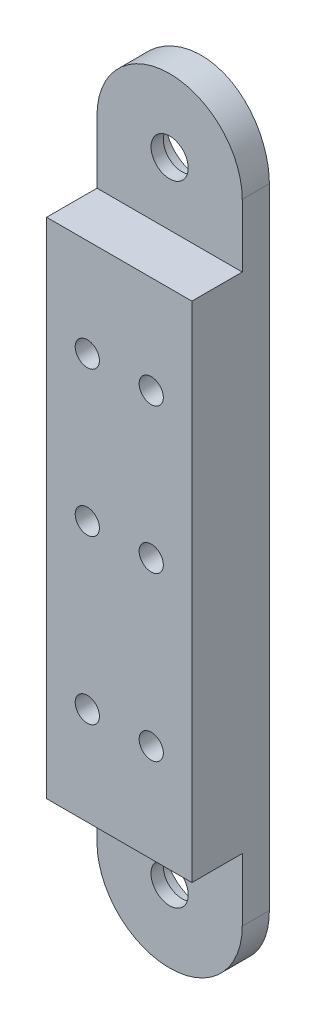
SolidWorks part; units mm, degrees
material "Nylon 101"
ref_plane "Front Plane" through (0, 0, 0) normal (0, 0, 1) x (1, 0, 0)
ref_plane "Top Plane" through (0, 0, 0) normal (0, 1, 0) x (1, 0, 0)
ref_plane "Right Plane" through (0, 0, 0) normal (1, 0, 0) x (0, 0, -1)
other "Stock"
other "Bounding Box"
ref_plane "Default Plane" through (5.3337, 0, -6.6488) normal (-1, 0, 0) x (0, 0, 1)
sketch "Sketch1" plane through (0, 0, 0) normal (0, 1, 0) x (1, 0, 0)
  line L1 (-4.1913, 1.27) -> (5.3337, 1.27)
  line L2 (-4.1913, 1.27) -> (-4.1913, 6.35)
  line L4 (5.3337, 1.27) -> (5.3337, 6.35)
  arc A0 (-4.1913, 6.35) -> (5.3337, 6.35) centre (0.5712, -31.4512) cw
  dimension "D3" = 38.1
  dimension "D1" = 9.525
  dimension "D2" = 5.08
extrude "Main profile" add sketch "Sketch1" along normal blind 50.8
sketch "Sketch2" plane through (0, 0, -1.27) normal (0, 0, 1) x (1, 0, 0)
  line L0 (-4.1913, 50.8) -> (-4.1913, 0) construction
  line L1 (5.3337, 50.8) -> (5.3337, 0) construction
  line L2 (-4.1913, 50.8) -> (5.3337, 50.8) construction
  line L3 (-4.1913, 0) -> (5.3337, 0) construction
  line L4 (-4.1913, 46.0375) -> (-4.1913, 4.7625)
  line L5 (5.3337, 46.0375) -> (5.3337, 4.7625)
  line L10 (-4.1913, 0) -> (5.3337, 0)
  line L11 (5.3337, 0) -> (5.3337, 50.8)
  line L12 (5.3337, 50.8) -> (-4.1913, 50.8)
  line L13 (-4.1913, 50.8) -> (-4.1913, 0)
  line L14 (-4.1913, 0) -> (5.3337, 0)
  line L15 (5.3337, 0) -> (5.3337, 50.8)
  line L16 (5.3337, 50.8) -> (-4.1913, 50.8)
  line L17 (-4.1913, 50.8) -> (-4.1913, 0)
  arc A0 (-4.1913, 46.0375) -> (5.3337, 46.0375) centre (0.5712, 46.0375) cw
  arc A1 (5.3337, 4.7625) -> (-4.1913, 4.7625) centre (0.5712, 4.7625) cw
  line M9 (-4.1913, 0) -> (5.3337, 0)
  line M10 (5.3337, 0) -> (5.3337, 50.8)
  line M11 (5.3337, 50.8) -> (-4.1913, 50.8)
  line M12 (-4.1913, 50.8) -> (-4.1913, 0)
  dimension "D2" = 4.7625
  dimension "D1" = 0
extrude "End rounds" cut sketch "Sketch2" against normal blind 25.4 contours A0 L16 M12 | A0 M11 M10 | A1 L14 M10 | A1 M9 M12
sketch "Sketch3" plane through (-4.1913, 0, 0) normal (-1, 0, 0) x (0, 0, 1)
  line L1 (-1.27, 46.0375) -> (-1.27, 50.8) construction
  line L4 (-1.27, 4.7625) -> (-1.27, 46.0375)
  line L7 (-1.27, 46.0375) -> (-6.35, 46.0375)
  line L8 (-1.27, 4.7625) -> (-1.27, 46.0375)
  line L12 (-1.27, 0) -> (-1.27, 4.7625) construction
  line L14 (-4.572, 25.4) -> (-1.27, 25.4) construction
  line L15 (-1.27, 46.0375) -> (-1.27, 50.8)
  line L17 (-4.572, 41.91) -> (-1.27, 41.91)
  line L18 (-1.27, 0) -> (-1.27, 4.7625)
  line L19 (-1.27, 8.89) -> (-4.572, 8.89)
  line L20 (-2.921, 8.89) -> (-2.921, 41.91) construction
  line L21 (-1.27, 50.8) -> (-4.572, 50.8)
  line L22 (-1.27, 50.8) -> (-1.27, 0)
  line L23 (-1.27, 0) -> (-4.572, 0)
  line L24 (-4.572, 50.8) -> (-4.572, 0)
  line L29 (-6.35, 4.7625) -> (-1.27, 4.7625)
  line L31 (-6.35, 46.0375) -> (-6.35, 4.7625)
  line L32 (-6.35, 46.0375) -> (-6.35, 4.7625)
  spline S0 degree 2 poles (-6.6488, 50.8) (-6.35, 48.4094) (-6.35, 46.0375) knots 0 0 0 0.468627 0.468627 0.468627 weights 0.033338 0.035569 0.037801 construction
  spline S1 degree 2 poles (-6.35, 4.7625) (-6.35, 2.3906) (-6.6488, 0) knots 0.468627 0.468627 0.468627 1 1 1 weights 0.037801 0.040332 0.042863 construction
  spline S2 degree 2 poles (-6.6488, 50.8) (-6.35, 48.4094) (-6.35, 46.0375) knots 0 0 0 0.468627 0.468627 0.468627 weights 0.033338 0.035569 0.037801
  spline S3 degree 2 poles (-6.35, 4.7625) (-6.35, 2.3906) (-6.6488, 0) knots 0.468627 0.468627 0.468627 1 1 1 weights 0.037801 0.040332 0.042863
  point P19 (-2.921, 25.4)
  line M11 (-1.27, 4.7625) -> (-1.27, 46.0375)
  line M12 (-1.27, 46.0375) -> (-6.35, 46.0375)
  line M14 (-6.35, 4.7625) -> (-1.27, 4.7625)
  dimension "D2" = 3.302
  dimension "D3" = 8.89
  dimension "D1" = 0
extrude "Locating Flange" cut sketch "Sketch3" against normal through all contours L24 L23 L18 M14 | L19 L24 M14 M11 | L24 L17 L8 M12 | L21 L24 L15 M12
ref_plane "Top Surface" through (0, 0, -6.6488) normal (0, 0, -1) x (-1, 0, 0)
sketch "Sketch4" plane through (0, 0, -6.6488) normal (0, 0, -1) x (-1, 0, 0)
  line L0 (-0.5712, 18.542) -> (-0.5712, 32.258) construction
  line L1 (-2.6827, 38.735) -> (1.5403, 38.735)
  line L2 (-5.3337, 46.0375) -> (-5.3337, 4.7625)
  line L6 (-3.8097, 37.608) -> (-3.8097, 33.385)
  line L7 (-2.6827, 32.258) -> (1.5403, 32.258)
  line L8 (2.6673, 37.608) -> (2.6673, 33.385)
  line L9 (-2.6827, 29.226) -> (1.5403, 29.226)
  line L14 (-3.8097, 28.099) -> (-3.8097, 23.876)
  line L16 (-2.6827, 22.749) -> (1.5403, 22.749)
  line L18 (4.1913, 8.89) -> (4.1913, 41.91)
  line L19 (-5.3337, 8.89) -> (4.1913, 8.89)
  line L20 (-5.3337, 41.91) -> (-5.3337, 8.89)
  line L21 (4.1913, 41.91) -> (-5.3337, 41.91)
  line L22 (4.1913, 8.89) -> (4.1913, 41.91)
  line L23 (-5.3337, 8.89) -> (4.1913, 8.89)
  line L24 (-5.3337, 41.91) -> (-5.3337, 8.89)
  line L25 (4.1913, 41.91) -> (-5.3337, 41.91)
  line L26 (2.6673, 28.099) -> (2.6673, 23.876)
  line L27 (-2.6827, 18.542) -> (1.5403, 18.542)
  line L28 (-3.8097, 17.415) -> (-3.8097, 13.192)
  line L29 (-2.6827, 12.065) -> (1.5403, 12.065)
  line L30 (2.6673, 17.415) -> (2.6673, 13.192)
  line L31 (-5.3337, 25.4) -> (4.1913, 25.4) construction
  line L34 (-5.3337, 46.0375) -> (-5.3337, 4.7625)
  line L36 (4.1913, 4.7625) -> (4.1913, 46.0375)
  line L37 (4.1913, 4.7625) -> (4.1913, 46.0375)
  arc A0 (1.5403, 12.065) -> (2.6673, 13.192) centre (1.5403, 13.192) ccw
  arc A1 (-3.8097, 13.192) -> (-2.6827, 12.065) centre (-2.6827, 13.192) ccw
  arc A2 (4.1913, 46.0375) -> (-5.3337, 46.0375) centre (-0.5712, 46.0375) ccw
  arc A3 (4.1913, 46.0375) -> (-5.3337, 46.0375) centre (-0.5712, 46.0375) ccw
  arc A6 (-5.3337, 4.7625) -> (4.1913, 4.7625) centre (-0.5712, 4.7625) ccw
  arc A7 (-5.3337, 4.7625) -> (4.1913, 4.7625) centre (-0.5712, 4.7625) ccw
  arc A8 (1.5403, 18.542) -> (2.6673, 17.415) centre (1.5403, 17.415) cw
  arc A9 (-2.6827, 18.542) -> (-3.8097, 17.415) centre (-2.6827, 17.415) ccw
  arc A10 (1.5403, 38.735) -> (2.6673, 37.608) centre (1.5403, 37.608) cw
  arc A11 (1.5403, 32.258) -> (2.6673, 33.385) centre (1.5403, 33.385) ccw
  arc A12 (-3.8097, 33.385) -> (-2.6827, 32.258) centre (-2.6827, 33.385) ccw
  arc A13 (1.5403, 22.749) -> (2.6673, 23.876) centre (1.5403, 23.876) ccw
  arc A14 (-2.6827, 29.226) -> (-3.8097, 28.099) centre (-2.6827, 28.099) ccw
  arc A15 (-3.8097, 23.876) -> (-2.6827, 22.749) centre (-2.6827, 23.876) ccw
  arc A16 (1.5403, 29.226) -> (2.6673, 28.099) centre (1.5403, 28.099) cw
  arc A17 (-2.6827, 38.735) -> (-3.8097, 37.608) centre (-2.6827, 37.608) ccw
  point P23 (-0.5712, 18.542)
  point P27 (-0.5712, 25.4)
  point P28 (-0.5712, 29.226)
  point P57 (-0.5712, 25.4)
  dimension "D6" = 1.127
  dimension "D4" = 3.175
  dimension "D5" = 3.175
  dimension "D7" = 6.477
  dimension "D1" = 0
  dimension "D3" = 0
extrude "Button Pockets" cut sketch "Sketch4" against normal blind 3.81 contours L16 L0 L9 L14 | L0 L16 L26 L9 | L30 L27 L28 L29 | L6 A12 L7 A11 L8 A10 L1 A17
sketch "Hole Locations" plane through (0, 0, -6.6488) normal (0, 0, -1) x (-1, 0, 0)
  line L2 (-5.3337, 46.0375) -> (-5.3337, 4.7625)
  line L6 (-5.3337, 46.0375) -> (-5.3337, 4.7625)
  line L8 (4.1913, 4.7625) -> (4.1913, 46.0375)
  line L9 (4.1913, 4.7625) -> (4.1913, 46.0375)
  arc A2 (4.1913, 46.0375) -> (-5.3337, 46.0375) centre (-0.5712, 46.0375) ccw
  arc A3 (-5.3337, 4.7625) -> (4.1913, 4.7625) centre (-0.5712, 4.7625) ccw
  arc A4 (4.1913, 46.0375) -> (-5.3337, 46.0375) centre (-0.5712, 46.0375) ccw
  arc A5 (-5.3337, 4.7625) -> (4.1913, 4.7625) centre (-0.5712, 4.7625) ccw
  point P5 (-0.5712, 46.0375)
  point P8 (-0.5712, 4.7625)
  dimension "D1" = 0
hole_wizard "CBORE for #2 Socket Head Cap Screw1" positions "Sketch7" profile "Sketch9" counterbore size "#2" standard "ANSI Inch" end condition through all
sketch "Sketch7" plane through (0, 0, -6.6488) normal (0, 0, -1) x (-1, 0, 0)
  point P0 (-0.5712, 46.0375)
  point P3 (-0.5712, 4.7625)
sketch "Sketch9" plane through (0.5712, 46.0375, -6.6488) normal (1, 0, 0) x (0, 1, 0)
  line L0 (0, 0) -> (0, 5.3788)
  line L1 (0, 5.3788) -> (1.2192, 5.3788)
  line L3 (1.2192, 5.3788) -> (1.2192, 1.27)
  line L4 (1.2192, 1.27) -> (2.286, 1.27)
  line L5 (2.286, 1.27) -> (2.286, 0)
  line L7 (2.286, 0) -> (0, 0)
  line L11 (0, -6.35) -> (0, 107.95) construction
  dimension "Thru Hole Dia." = 2.4384
  dimension "Thru Hole Depth" = 5.3788
  dimension "C'Bore Dia." = 4.572
  dimension "C'Bore Depth" = 1.27
sketch "Sketch13" plane through (0, 0, -1.27) normal (0, 0, 1) x (1, 0, 0)
  line L0 (-1.5403, 18.542) -> (2.6827, 18.542) construction
  line L1 (3.8097, 17.415) -> (3.8097, 13.192) construction
  line L2 (2.6827, 12.065) -> (-1.5403, 12.065) construction
  line L3 (-2.6673, 13.192) -> (-2.6673, 17.415) construction
  line L4 (-1.5403, 29.226) -> (2.6827, 29.226) construction
  line L5 (3.8097, 28.099) -> (3.8097, 23.876) construction
  line L6 (2.6827, 22.749) -> (-1.5403, 22.749) construction
  line L7 (-2.6673, 23.876) -> (-2.6673, 28.099) construction
  line L8 (3.8097, 37.608) -> (3.8097, 33.385) construction
  line L9 (2.6827, 32.258) -> (-1.5403, 32.258) construction
  line L10 (-2.6673, 33.385) -> (-2.6673, 37.608) construction
  line L11 (-1.5403, 38.735) -> (2.6827, 38.735) construction
  line L12 (-4.1913, 41.91) -> (-4.1913, 8.89) construction
  line L13 (-4.1913, 8.89) -> (5.3337, 8.89) construction
  line L14 (5.3337, 8.89) -> (5.3337, 41.91) construction
  line L15 (5.3337, 41.91) -> (-4.1913, 41.91) construction
  line L16 (-1.5403, 18.542) -> (2.6827, 18.542)
  line L17 (3.8097, 17.415) -> (3.8097, 13.192)
  line L18 (2.6827, 12.065) -> (-1.5403, 12.065)
  line L19 (-2.6673, 13.192) -> (-2.6673, 17.415)
  line L20 (-1.5403, 29.226) -> (2.6827, 29.226)
  line L21 (3.8097, 28.099) -> (3.8097, 23.876)
  line L22 (2.6827, 22.749) -> (-1.5403, 22.749)
  line L23 (-2.6673, 23.876) -> (-2.6673, 28.099)
  line L24 (3.8097, 37.608) -> (3.8097, 33.385)
  line L25 (2.6827, 32.258) -> (-1.5403, 32.258)
  line L26 (-2.6673, 33.385) -> (-2.6673, 37.608)
  line L27 (-1.5403, 38.735) -> (2.6827, 38.735)
  line L28 (-4.1913, 41.91) -> (-4.1913, 8.89)
  line L29 (-4.1913, 8.89) -> (5.3337, 8.89)
  line L30 (5.3337, 8.89) -> (5.3337, 41.91)
  line L31 (5.3337, 41.91) -> (-4.1913, 41.91)
  line L32 (-1.5243, 35.4965) -> (2.6667, 35.4965) construction
  arc A0 (3.8097, 17.415) -> (2.6827, 18.542) centre (2.6827, 17.415) ccw construction
  arc A1 (2.6827, 12.065) -> (3.8097, 13.192) centre (2.6827, 13.192) ccw construction
  arc A2 (-2.6673, 13.192) -> (-1.5403, 12.065) centre (-1.5403, 13.192) ccw construction
  arc A3 (-1.5403, 18.542) -> (-2.6673, 17.415) centre (-1.5403, 17.415) ccw construction
  arc A4 (-1.5403, 29.226) -> (-2.6673, 28.099) centre (-1.5403, 28.099) ccw construction
  arc A5 (3.8097, 28.099) -> (2.6827, 29.226) centre (2.6827, 28.099) ccw construction
  arc A6 (2.6827, 22.749) -> (3.8097, 23.876) centre (2.6827, 23.876) ccw construction
  arc A7 (-2.6673, 23.876) -> (-1.5403, 22.749) centre (-1.5403, 23.876) ccw construction
  arc A8 (3.8097, 37.608) -> (2.6827, 38.735) centre (2.6827, 37.608) ccw construction
  arc A9 (2.6827, 32.258) -> (3.8097, 33.385) centre (2.6827, 33.385) ccw construction
  arc A10 (-2.6673, 33.385) -> (-1.5403, 32.258) centre (-1.5403, 33.385) ccw construction
  arc A11 (-1.5403, 38.735) -> (-2.6673, 37.608) centre (-1.5403, 37.608) ccw construction
  arc A12 (3.8097, 17.415) -> (2.6827, 18.542) centre (2.6827, 17.415) ccw
  arc A13 (2.6827, 12.065) -> (3.8097, 13.192) centre (2.6827, 13.192) ccw
  arc A14 (-2.6673, 13.192) -> (-1.5403, 12.065) centre (-1.5403, 13.192) ccw
  arc A15 (-1.5403, 18.542) -> (-2.6673, 17.415) centre (-1.5403, 17.415) ccw
  arc A16 (-1.5403, 29.226) -> (-2.6673, 28.099) centre (-1.5403, 28.099) ccw
  arc A17 (3.8097, 28.099) -> (2.6827, 29.226) centre (2.6827, 28.099) ccw
  arc A18 (2.6827, 22.749) -> (3.8097, 23.876) centre (2.6827, 23.876) ccw
  arc A19 (-2.6673, 23.876) -> (-1.5403, 22.749) centre (-1.5403, 23.876) ccw
  arc A20 (3.8097, 37.608) -> (2.6827, 38.735) centre (2.6827, 37.608) ccw
  arc A21 (2.6827, 32.258) -> (3.8097, 33.385) centre (2.6827, 33.385) ccw
  arc A22 (-2.6673, 33.385) -> (-1.5403, 32.258) centre (-1.5403, 33.385) ccw
  arc A23 (-1.5403, 38.735) -> (-2.6673, 37.608) centre (-1.5403, 37.608) ccw
  point P4 (-1.5243, 35.4965)
  point P5 (2.6667, 35.4965)
  point P9 (2.6667, 25.9875)
  point P10 (2.6667, 15.3035)
  point P14 (-1.5243, 15.3035)
  point P15 (-1.5243, 25.9875)
  point P18 (0.5712, 35.4965)
  point P19 (0.5712, 41.91)
  point P27 (3.8097, 25.9875)
  point P37 (3.8097, 15.3035)
  point P39 (3.8097, 35.4965)
  dimension "D1" = 4.191
hole_wizard "1/16 (0.0625) Diameter Hole1" positions "Sketch14" profile "Sketch16" hole size "1/16" standard "ANSI Inch" end condition through all
sketch "Sketch14" plane through (0, 0, -1.27) normal (0, 0, 1) x (1, 0, 0)
  point P0 (-1.5243, 35.4965)
  point P3 (2.6667, 35.4965)
  point P6 (2.6667, 25.9875)
  point P9 (-1.5243, 25.9875)
  point P12 (-1.5243, 15.3035)
  point P15 (2.6667, 15.3035)
sketch "Sketch16" plane through (-1.5243, 35.4965, -1.27) normal (1, 0, 0) x (0, -1, 0)
  line L0 (0, 0) -> (0, 5.3788)
  line L1 (0, 5.3788) -> (0.7937, 5.3788)
  line L2 (0.7937, 5.3788) -> (0.7937, 0)
  line L5 (0.7937, 0) -> (0, 0)
  line L11 (0, -6.35) -> (0, 107.95) construction
  dimension "Thru Hole Dia." = 1.5875
  dimension "Thru Hole Depth" = 5.3788
